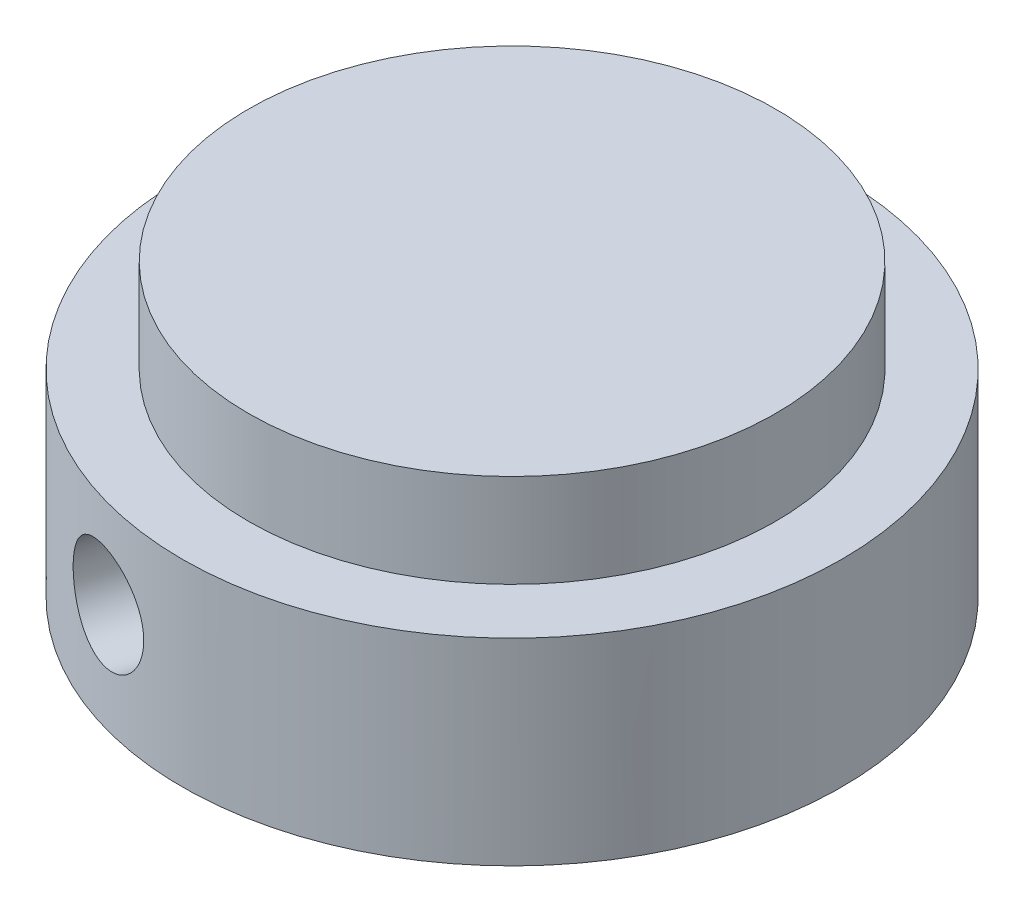
SolidWorks part; units mm, degrees
ref_plane "Front Plane" through (0, 0, 0) normal (0, 0, 1) x (1, 0, 0)
ref_plane "Top Plane" through (0, 0, 0) normal (0, 1, 0) x (1, 0, 0)
ref_plane "Right Plane" through (0, 0, 0) normal (1, 0, 0) x (0, 0, -1)
sketch "Sketch1" plane through (0, 0, 0) normal (0, 1, 0) x (1, 0, 0)
  circle A0 centre (0, 0) radius 6.35
  dimension "D1" = 12.7
extrude "Boss-Extrude1" add sketch "Sketch1" along normal blind 6.95
sketch "Sketch2" plane through (0, 0, 0) normal (0, -1, 0) x (1, 0, 0)
  circle A0 centre (0, 0) radius 4
  circle A1 centre (0, 0) radius 7.5427
  dimension "D1" = 8
extrude "Cut-Extrude1" cut sketch "Sketch2" against normal blind 1.35 contours A1 | A0
sketch "Sketch3" plane through (0, 6.95, 0) normal (0, 1, 0) x (1, 0, 0)
  circle A0 centre (0, 0) radius 5.08
  circle A1 centre (0, 0) radius 7.4195
  dimension "D1" = 10.16
extrude "Cut-Extrude2" cut sketch "Sketch3" against normal blind 1.8 contours A1 | A0
hole_wizard "Ø2.0mm Dowel Hole1" positions "3DSketch1" profile "Sketch4" hole size "Ø2.0" standard "ISO"
sketch3d "3DSketch1"
  point P0 (-1.7794, 3.37, 6.0956)
  dimension "D1" = 3.58
sketch "Sketch4" plane through (-1.7794, 3.37, 6.0956) normal (0, 1, 0) x (0.9599, 0, 0.2802)
  line L0 (0, 0) -> (0, 2.6009)
  line L1 (0, 2.6009) -> (1, 2)
  line L2 (1, 2) -> (1, 0)
  line L5 (1, 0) -> (0, 0)
  line L10 (0, 2.6009) -> (-1, 2) construction
  line L11 (0, -6.35) -> (0, 107.95) construction
  dimension "Hole Dia." = 2
  dimension "Hole Depth" = 2
  dimension "Drill Angle" = 118
